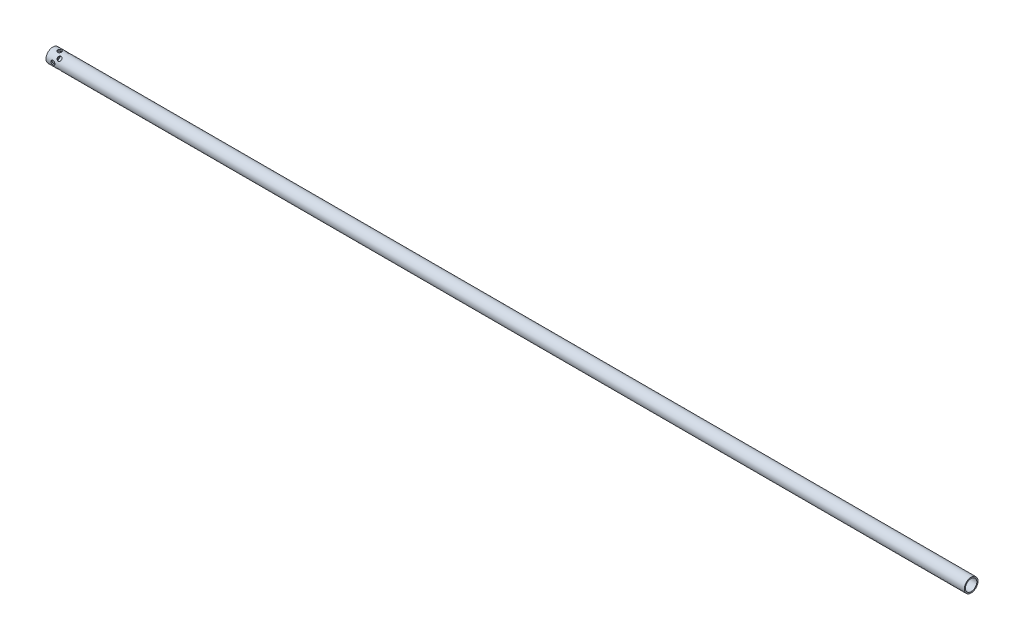
SolidWorks part; units mm, degrees
material "6061-T6 (SS)"
ref_plane "Front" through (0, 0, 0) normal (0, 0, 1) x (1, 0, 0)
ref_plane "Top" through (0, 0, 0) normal (0, 1, 0) x (1, 0, 0)
ref_plane "Right" through (0, 0, 0) normal (1, 0, 0) x (0, 0, -1)
sketch "Sketch1" plane through (0, 0, 0) normal (1, 0, 0) x (0, 0, -1)
  circle A0 centre (0, 0) radius 9.525
  circle A1 centre (0, 0) radius 7.874
  dimension "D1" = 19.05
  dimension "D2" = 1.651
extrude "Boss-Extrude1" add sketch "Sketch1" along normal blind 1270
sketch "Sketch2" plane through (0, 0, 0) normal (1, 0, 0) x (0, 0, -1)
  circle A0 centre (0, 0) radius 9.525
extrude "Boss-Extrude2" add sketch "Sketch2" against normal blind 3.175
sketch "Sketch3" plane through (0, 0, 0) normal (0, 0, 1) x (1, 0, 0)
  line L0 (0, 0) -> (71.7681, 0) construction
  line L1 (-35.8841, 0) -> (35.8841, 0) construction
  circle A0 centre (6.35, 0) radius 2.7781
  dimension "D1" = 5.5562
  dimension "D2" = 6.35
extrude "Cut-Extrude1" cut sketch "Sketch3" against normal mid plane 25.4
pattern_circular "CirPattern1" count 2 every 90 about axis through (1270, 0, 0) along (-1, 0, 0) of "Cut-Extrude1"
ref_plane "Plane1" through (0, 0, 0) normal (0, -0.7071, 0.7071) x (1, 0, 0)
sketch "Sketch4" plane through (0, 0, 0) normal (0, -0.7071, 0.7071) x (1, 0, 0)
  line L0 (-35.8841, 0) -> (35.8841, 0) construction
  line L1 (0, 0) -> (71.7681, 0) construction
  circle A0 centre (12.7, 0) radius 2.7781
  dimension "D1" = 12.7
extrude "Cut-Extrude2" cut sketch "Sketch4" against normal mid plane 25.4 contours A0
pattern_circular "CirPattern2" count 2 every 90 about axis through (1270, 0, 0) along (-1, 0, 0) of "Cut-Extrude2"
